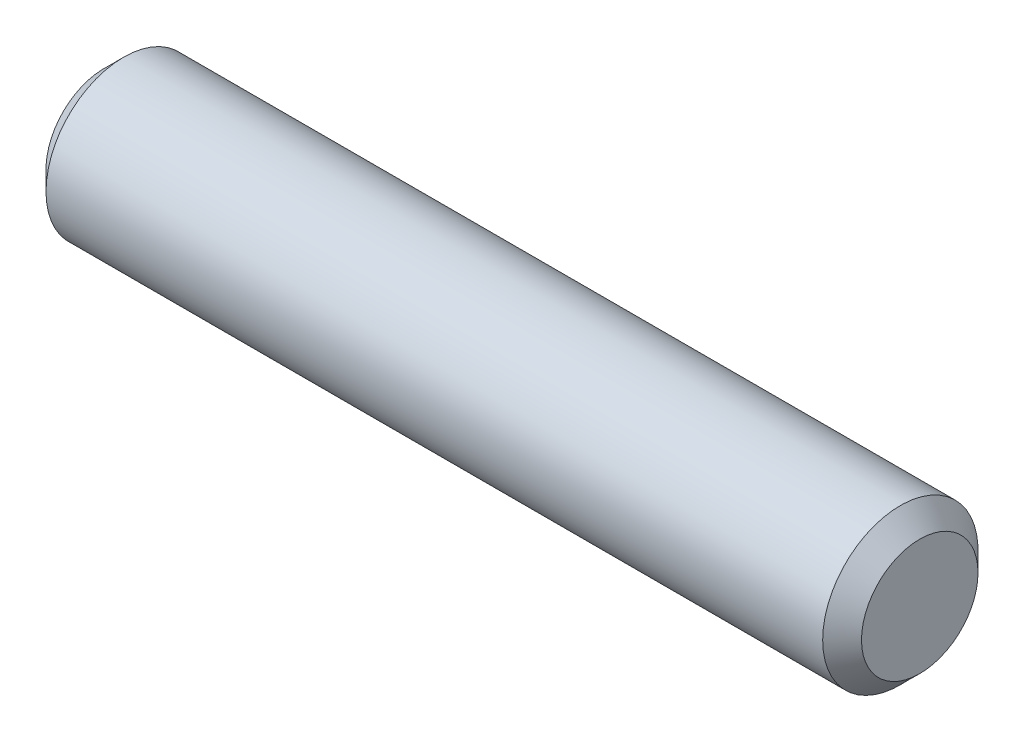
SolidWorks part; units mm, degrees
ref_plane "Plan de face" through (0, 0, 0) normal (0, 0, 1) x (1, 0, 0)
ref_plane "Plan de dessus" through (0, 0, 0) normal (0, 1, 0) x (1, 0, 0)
ref_plane "Plan de droite" through (0, 0, 0) normal (1, 0, 0) x (0, 0, -1)
sketch "Esquisse1" plane through (0, 0, 0) normal (1, 0, 0) x (0, 0, -1)
  circle A0 centre (0, 0) radius 2
  dimension "D1" = 4
extrude "Boss.-Extru.1" add sketch "Esquisse1" along normal mid plane 21
chamfer "Chanfrein1" distance 0.5 angle 45 2 edges at (10.5, 0, -2) (-10.5, 0, -2)
